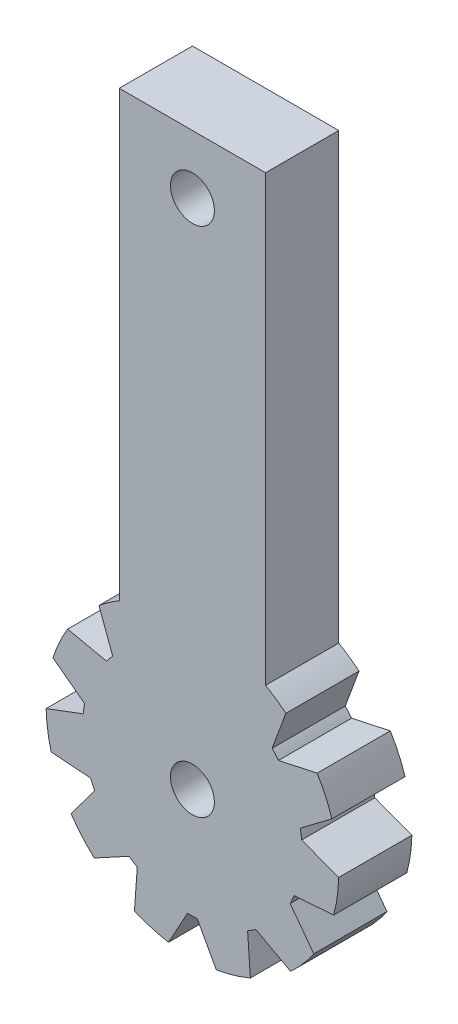
SolidWorks part; units mm, degrees
ref_plane "Front Plane" through (0, 0, 0) normal (0, 0, 1) x (1, 0, 0)
ref_plane "Top Plane" through (0, 0, 0) normal (0, 1, 0) x (1, 0, 0)
ref_plane "Right Plane" through (0, 0, 0) normal (1, 0, 0) x (0, 0, -1)
sketch "Sketch1" plane through (0, 0, 0) normal (0, 0, 1) x (1, 0, 0)
  line L0 (0, 11.2329) -> (0, -11.9005) construction
  line L1 (-1.7923, 7.2827) -> (-1.2129, 9.9262)
  line L2 (1.7923, 7.2827) -> (1.2129, 9.9262)
  line L3 (2.4295, 7.0956) -> (4.3461, 9.0062)
  line L4 (5.4451, 5.1576) -> (6.3869, 7.6947)
  line L5 (5.88, 4.6557) -> (8.5253, 5.2268)
  line L6 (7.3691, 1.395) -> (9.533, 3.0202)
  line L7 (7.4636, 0.7376) -> (9.9978, -0.2121)
  line L8 (6.9535, -2.8105) -> (9.6525, -2.6132)
  line L9 (6.6776, -3.4146) -> (8.296, -5.5836)
  line L10 (4.3302, -6.1237) -> (6.7074, -7.4169)
  line L11 (3.7715, -6.4827) -> (3.9603, -9.1824)
  line L12 (0.3321, -7.4926) -> (1.6327, -9.8658)
  line L13 (-0.3321, -7.4926) -> (-1.6327, -9.8658)
  line L14 (-3.7715, -6.4827) -> (-3.9603, -9.1824)
  line L15 (-4.3302, -6.1237) -> (-6.7074, -7.4169)
  line L16 (-6.6776, -3.4146) -> (-8.296, -5.5836)
  line L17 (-6.9535, -2.8105) -> (-9.6525, -2.6132)
  line L18 (-7.4636, 0.7376) -> (-9.9978, -0.2121)
  line L19 (-7.3691, 1.395) -> (-9.533, 3.0202)
  line L20 (-5.88, 4.6557) -> (-8.5253, 5.2268)
  line L21 (-5.4451, 5.1576) -> (-6.3869, 7.6947)
  line L22 (-2.4295, 7.0956) -> (-4.3461, 9.0062)
  arc A0 (-5.4451, 5.1576) -> (-5.88, 4.6557) centre (0, 0) ccw
  circle A1 centre (0, 0) radius 8.7846 construction
  arc A2 (1.2129, 9.9262) -> (-1.2129, 9.9262) centre (0, 0) ccw
  arc A3 (6.3869, 7.6947) -> (4.3461, 9.0062) centre (0, 0) ccw
  arc A4 (9.533, 3.0202) -> (8.5253, 5.2268) centre (0, 0) ccw
  arc A5 (9.6525, -2.6132) -> (9.9978, -0.2121) centre (0, 0) ccw
  arc A6 (6.7074, -7.4169) -> (8.296, -5.5836) centre (0, 0) ccw
  arc A7 (1.6327, -9.8658) -> (3.9603, -9.1824) centre (0, 0) ccw
  arc A8 (-3.9603, -9.1824) -> (-1.6327, -9.8658) centre (0, 0) ccw
  arc A9 (-8.296, -5.5836) -> (-6.7074, -7.4169) centre (0, 0) ccw
  arc A10 (-9.9978, -0.2121) -> (-9.6525, -2.6132) centre (0, 0) ccw
  arc A11 (-8.5253, 5.2268) -> (-9.533, 3.0202) centre (0, 0) ccw
  arc A12 (-4.3461, 9.0062) -> (-6.3869, 7.6947) centre (0, 0) ccw
  arc A13 (-7.3691, 1.395) -> (-7.4636, 0.7376) centre (0, 0) ccw
  arc A14 (2.4295, 7.0956) -> (-2.4295, 7.0956) centre (0, 0) ccw
  arc A15 (5.88, 4.6557) -> (5.4451, 5.1576) centre (0, 0) ccw
  arc A16 (7.4636, 0.7376) -> (7.3691, 1.395) centre (0, 0) ccw
  arc A17 (6.6776, -3.4146) -> (6.9535, -2.8105) centre (0, 0) ccw
  arc A18 (3.7715, -6.4827) -> (4.3302, -6.1237) centre (0, 0) ccw
  arc A19 (-0.3321, -7.4926) -> (0.3321, -7.4926) centre (0, 0) ccw
  arc A20 (-4.3302, -6.1237) -> (-3.7715, -6.4827) centre (0, 0) ccw
  arc A21 (-6.9535, -2.8105) -> (-6.6776, -3.4146) centre (0, 0) ccw
  point P54 (0, 0)
  dimension "D1" = 15
  dimension "D2" = 20
  dimension "D3" = 11
extrude "Boss-Extrude1" add sketch "Sketch1" along normal blind 5 contours A0 | A2 A0
sketch "Sketch5" plane through (0, 0, 0) normal (0, 0, -1) x (-1, 0, 0)
  circle A0 centre (0, 0) radius 2.425
  dimension "D1" = 4.85
extrude "Cut-Extrude2" cut sketch "Sketch5" against normal blind 2.7
sketch "Sketch6" plane through (0, 0, 2.7) normal (0, 0, -1) x (-1, 0, 0)
  circle A0 centre (0, 0) radius 1.5
  dimension "D1" = 3
extrude "Cut-Extrude3" cut sketch "Sketch6" against normal blind 12
sketch "Sketch7" plane through (0, 0, 0) normal (0, 0, -1) x (-1, 0, 0)
  line L1 (-5, 4) -> (5, 4)
  line L2 (-5, 4) -> (-5, 39)
  line L3 (-5, 39) -> (5, 39)
  line L4 (5, 4) -> (5, 39)
  point P4 (0, 4)
  dimension "D1" = 10
  dimension "D2" = 35
  dimension "D3" = 4
extrude "Boss-Extrude3" add sketch "Sketch7" against normal up to surface (5 mm away) up to face at (1.5, 0, 5)
sketch "Sketch8" plane through (0, 0, 0) normal (0, 0, -1) x (-1, 0, 0)
  circle A0 centre (0, 35) radius 1.5
  dimension "D1" = 3
  dimension "D2" = 35
extrude "Cut-Extrude4" cut sketch "Sketch8" against normal blind 12
